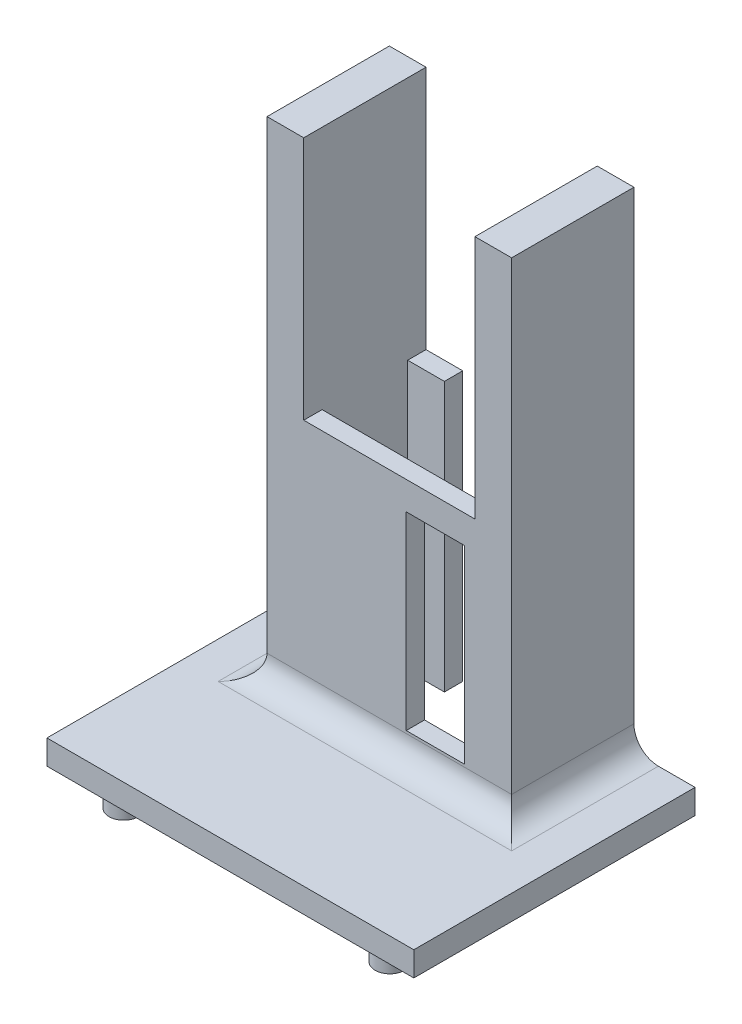
SolidWorks part; units mm, degrees
material "ABS PC"
ref_plane "Front Plane" through (0, 0, 0) normal (0, 0, 1) x (1, 0, 0)
ref_plane "Top Plane" through (0, 0, 0) normal (0, 1, 0) x (1, 0, 0)
ref_plane "Right Plane" through (0, 0, 0) normal (1, 0, 0) x (0, 0, -1)
sketch "Sketch1" plane through (0, 0, 0) normal (0, 1, 0) x (1, 0, 0)
  line L0 (-12.7, 6.35) -> (-5.08, 6.35)
  line L1 (12.7, -6.35) -> (-12.7, -6.35)
  line L2 (12.7, -6.35) -> (12.7, 6.35)
  line L3 (-5.08, 6.35) -> (-5.08, 4.445)
  line L4 (-12.7, -6.35) -> (-12.7, 6.35)
  line L5 (12.7, -6.35) -> (-12.7, 6.35) construction
  line L6 (12.7, 6.35) -> (-12.7, -6.35) construction
  line L7 (-5.08, 4.445) -> (-8.89, 4.445)
  line L8 (-8.89, 4.445) -> (-8.89, -4.445)
  line L9 (-8.89, -4.445) -> (8.89, -4.445)
  line L10 (8.89, -4.445) -> (8.89, 4.445)
  line L11 (8.89, 4.445) -> (5.08, 4.445)
  line L12 (5.08, 4.445) -> (5.08, 6.35)
  line L13 (5.08, 6.35) -> (12.7, 6.35)
  point P0 (0, 0)
  point P6 (-24.5641, -16.9902)
  point P15 (19.0956, -13.2078)
  point P16 (23.4361, -16.3256)
  point P17 (23.1808, 16.1477)
  point P18 (-24.8194, 17.2892)
  dimension "D1" = 7.62
  dimension "D2" = 7.62
  dimension "D3" = 25.4
  dimension "D4" = 12.7
  dimension "D5" = 3.81
  dimension "D6" = 1.905
extrude "Boss-Extrude1" add sketch "Sketch1" along normal blind 25.4
sketch "Sketch2" plane through (0, 0, 0) normal (0, -1, 0) x (1, 0, 0)
  line L0 (-12.7, -6.35) -> (-19.05, -6.35)
  line L1 (-19.05, -6.35) -> (-19.05, 22.86)
  line L2 (-19.05, 22.86) -> (19.05, 22.86)
  line L3 (19.05, 22.86) -> (19.05, -6.35)
  line L4 (19.05, -6.35) -> (12.7, -6.35)
  line L5 (-12.7, -6.35) -> (-12.7, 6.35) construction
  line L6 (-12.7, 6.35) -> (12.7, 6.35) construction
  line L12 (-12.7, 6.35) -> (-12.7, -6.35)
  line L13 (-12.7, -6.35) -> (-5.08, -6.35)
  line L14 (-5.08, -6.35) -> (-5.08, -4.445)
  line L15 (-5.08, -4.445) -> (-8.89, -4.445)
  line L16 (-8.89, -4.445) -> (-8.89, 4.445)
  line L17 (-8.89, 4.445) -> (8.89, 4.445)
  line L18 (8.89, 4.445) -> (8.89, -4.445)
  line L19 (8.89, -4.445) -> (5.08, -4.445)
  line L20 (5.08, -4.445) -> (5.08, -6.35)
  line L21 (5.08, -6.35) -> (12.7, -6.35)
  line L22 (12.7, -6.35) -> (12.7, 6.35)
  line L23 (12.7, 6.35) -> (-12.7, 6.35)
  line L25 (-12.7, -6.35) -> (-5.08, -6.35)
  line L26 (-5.08, -6.35) -> (-5.08, -4.445)
  line L27 (-5.08, -4.445) -> (-8.89, -4.445)
  line L28 (-8.89, -4.445) -> (-8.89, 4.445)
  line L29 (-8.89, 4.445) -> (8.89, 4.445)
  line L30 (8.89, 4.445) -> (8.89, -4.445)
  line L31 (8.89, -4.445) -> (5.08, -4.445)
  line L32 (5.08, -4.445) -> (5.08, -6.35)
  line L33 (5.08, -6.35) -> (12.7, -6.35)
  dimension "D2" = 6.35
  dimension "D3" = 16.51
  dimension "D4" = 6.35
  dimension "D1" = 0
extrude "Boss-Extrude2" add sketch "Sketch2" along normal blind 2.54
fillet "Fillet1" radius 2.54 3 edges at (12.7, 0, 0) (0, 0, 6.35) (-12.7, 0, 0)
sketch "Sketch3" plane through (0, -2.54, 0) normal (0, -1, 0) x (1, 0, 0)
  line L0 (0, 0) -> (0, 22.86) construction
  line L1 (19.05, 22.86) -> (-19.05, 22.86) construction
  line L2 (-19.05, -6.35) -> (-5.08, -6.35) construction
  line L3 (-19.05, 22.86) -> (-19.05, -6.35) construction
  circle A0 centre (-13.8176, -0.4318) radius 1.524
  dimension "D1" = 3.048
  dimension "D2" = 5.9182
  dimension "D3" = 5.2324
extrude "Boss-Extrude3" add sketch "Sketch3" along normal blind 2.54
sketch "Sketch4" plane through (0, -2.54, 0) normal (0, -1, 0) x (-1, 0, 0)
  line L0 (15.7226, -6.096) -> (13.8176, 0.4318) construction
  line L1 (15.7226, -14.986) -> (11.9126, -14.986)
  line L2 (15.7226, -14.986) -> (15.7226, -6.096)
  line L3 (15.7226, -6.096) -> (11.9126, -6.096)
  line L4 (11.9126, -14.986) -> (11.9126, -6.096)
  line L5 (13.8176, 0.4318) -> (11.9126, -6.096) construction
  line L6 (11.9126, -10.541) -> (15.7226, -10.541) construction
  circle A0 centre (13.8176, 0.4318) radius 1.524 construction
  circle A1 centre (13.8176, -20.1168) radius 1.524
  point P4 (13.8176, -14.986)
  point P6 (13.8176, -6.096)
  dimension "D1" = 6.5278
  dimension "D4" = 3.048
  dimension "D5" = 5.1308
  dimension "D2" = 8.89
  dimension "D3" = 3.81
extrude "Boss-Extrude4" add sketch "Sketch4" along normal blind 2.54
mirror "Mirror1" about plane through (0, 0, 0) normal (1, 0, 0) of "Boss-Extrude3", "Boss-Extrude4"
sketch "Sketch5" plane through (0, 0, 6.35) normal (0, 0, 1) x (1, 0, 0)
  line L1 (1.7513, 22.4801) -> (7.779, 22.4801)
  line L2 (1.7513, 22.4801) -> (1.7513, 2.8086)
  line L3 (1.7513, 2.8086) -> (7.779, 2.8086)
  line L4 (7.779, 22.4801) -> (7.779, 2.8086)
extrude "Cut-Extrude1" cut sketch "Sketch5" against normal up to next
sketch "Sketch6" plane through (0, 25.4, 0) normal (0, 1, 0) x (1, 0, 0)
  line L0 (-12.7, -6.35) -> (12.7, -6.35) construction
  line L1 (-12.7, 6.35) -> (-8.89, 6.35)
  line L2 (-12.7, 6.35) -> (-12.7, -6.35)
  line L3 (-12.7, -6.35) -> (-8.89, -6.35)
  line L4 (-8.89, 6.35) -> (-8.89, -6.35)
  line L5 (12.7, 6.35) -> (5.08, 6.35) construction
  line L6 (12.7, -6.35) -> (8.89, -6.35)
  line L7 (12.7, -6.35) -> (12.7, 6.35)
  line L8 (12.7, 6.35) -> (8.89, 6.35)
  line L9 (8.89, -6.35) -> (8.89, 6.35)
  line L10 (-8.89, -4.445) -> (-8.89, 4.445) construction
  point P14 (0, 0)
extrude "Boss-Extrude5" add sketch "Sketch6" along normal blind 25.4
